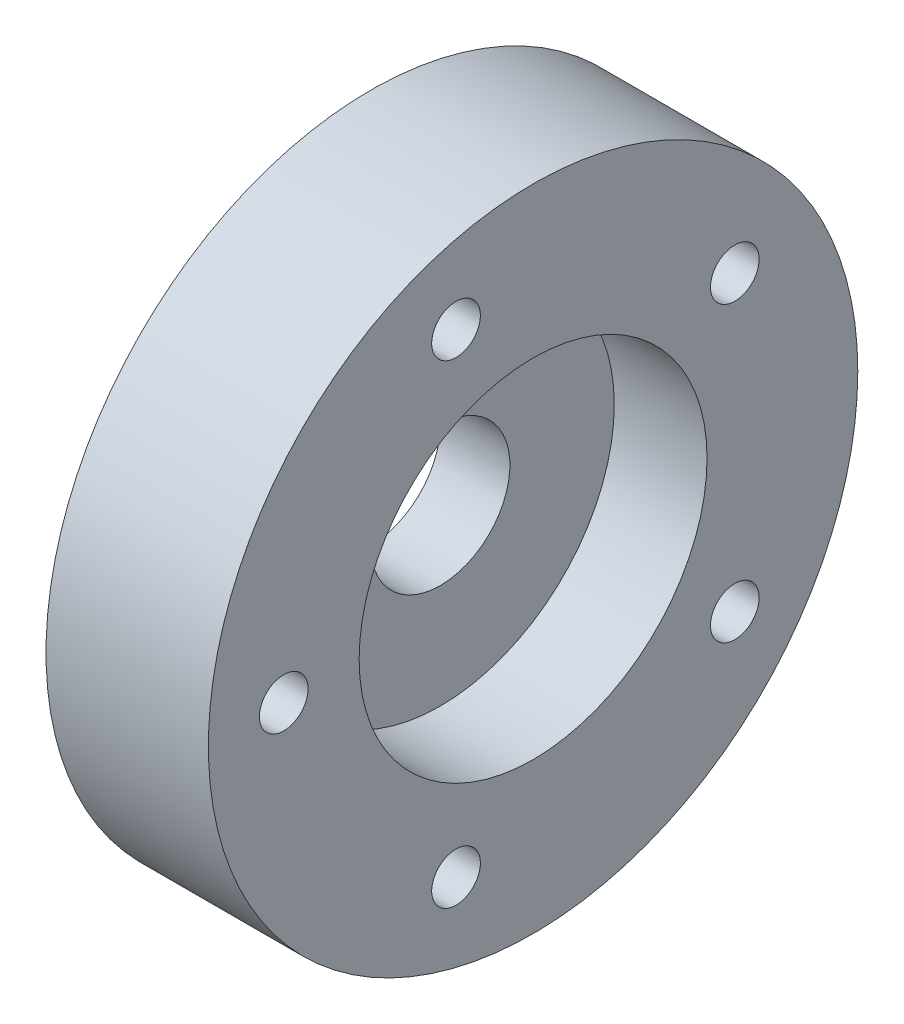
SolidWorks part; units mm, degrees
material "6061-T6 (SS)"
ref_plane "Front Plane" through (0, 0, 0) normal (1, 0, 0) x (0, 1, 0)
ref_plane "Top Plane" through (0, 0, 0) normal (0, 0, 1) x (0, 1, 0)
ref_plane "Right Plane" through (0, 0, 0) normal (0, 1, 0) x (-1, 0, 0)
sketch "Sketch1" plane through (0, 0, 0) normal (1, 0, 0) x (0, 1, 0)
  circle A0 centre (0, 0) radius 28
  dimension "D1" = 56
extrude "Boss-Extrude1" add sketch "Sketch1" along normal blind 14
sketch "Sketch2" plane through (14, 0, 0) normal (1, 0, 0) x (0, 1, 0)
  circle A0 centre (0, 0) radius 15
  dimension "D1" = 30
extrude "Cut-Extrude1" cut sketch "Sketch2" against normal blind 8
sketch "Sketch3" plane through (0, 0, 0) normal (-1, 0, 0) x (0, -1, 0)
  line L0 (0, 0) -> (0, 7.5) construction
  line L1 (-2, 7.5) -> (2, 7.5)
  line L2 (-2, 7.5) -> (-2, 5.6569)
  line L3 (2, 7.5) -> (2, 5.6569)
  arc A0 (-2, 5.6569) -> (2, 5.6569) centre (0, 0) ccw
  point P7 (0, 7.5)
  dimension "D1" = 12
  dimension "D2" = 4
  dimension "D3" = 7.5
extrude "Cut-Extrude2" cut sketch "Sketch3" against normal blind 16
sketch "Sketch9" plane through (14, 0, 0) normal (1, 0, 0) x (0, 1, 0)
  circle A1 centre (0, 0) radius 21.5 construction
  circle A2 centre (0, 21.5) radius 1.5
  circle A3 centre (20.4477, 6.6439) radius 1.5
  circle A4 centre (12.6374, -17.3939) radius 1.5
  circle A5 centre (-12.6374, -17.3939) radius 1.5
  circle A6 centre (-20.4477, 6.6439) radius 1.5
  point P15 (0, 0)
  dimension "D1" = 3
  dimension "D2" = 43
  dimension "D3" = 5
hole_wizard "M5x0.8 Tapped Hole1" positions "3DSketch5" profile "Sketch10" tap size "M5x0.8" standard "ANSI Metric"
sketch3d "3DSketch5"
  point P0 (14, -20.4477, 6.6439)
  point P3 (14, 0, 21.5)
  point P6 (14, -12.6374, -17.3939)
  point P9 (14, 12.6374, -17.3939)
  point P12 (14, 20.4477, 6.6439)
sketch "Sketch10" plane through (14, -20.4477, 6.6439) normal (0, 1, 0) x (0, 0, -1)
  line L0 (0, 0) -> (0, 9.2618)
  line L1 (0, 9.2618) -> (2.1, 8)
  line L2 (2.1, 8) -> (2.1, 0)
  line L5 (2.1, 0) -> (0, 0)
  line L10 (0, 9.2618) -> (-2.1, 8) construction
  line L11 (0, -6.35) -> (0, 107.95) construction
  dimension "Tap Drill Dia." = 4.2
  dimension "Tap Drill Depth" = 8
  dimension "Drill Angle" = 118
